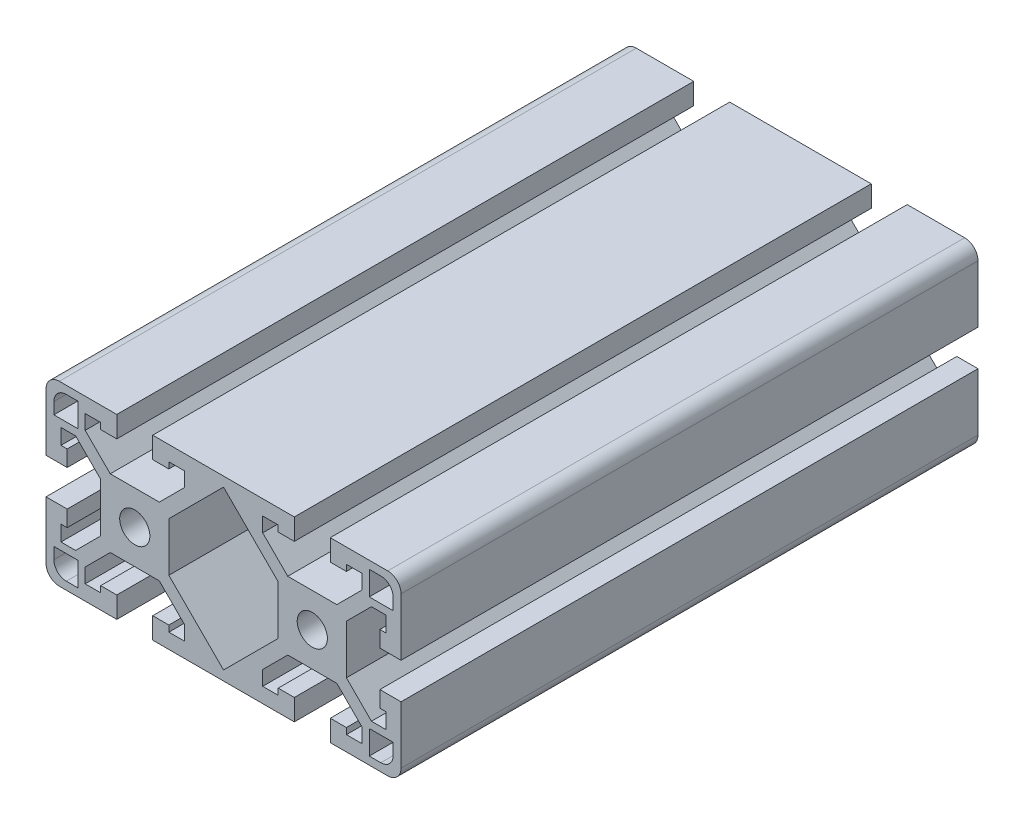
SolidWorks part; units mm, degrees
material "6063-T5"
ref_plane "Front Plane" through (0, 0, 0) normal (0, 0, 1) x (1, 0, 0)
ref_plane "Top Plane" through (0, 0, 0) normal (0, 1, 0) x (1, 0, 0)
ref_plane "Right Plane" through (0, 0, 0) normal (1, 0, 0) x (0, 0, -1)
sketch "Sketch1" plane through (0, 0, 0) normal (0, 1, 0) x (1, 0, 0)
  line L0 (0, 130) -> (0, 0)
  dimension "D1" = 130
other "40 series TS40-80LM-650037(1)"
ref_plane "Plane1" through (0, 0, -130) normal (0, 0, 1) x (0, 1, 0)
sketch "Sketch2" plane through (0, 0, -130) normal (0, 0, 1) x (0, 1, 0)
  line L2 (0, -27.681) -> (-5.5257, -27.681)
  line L3 (-5.5257, -27.681) -> (-11.176, -33.3313)
  line L4 (-7.6835, -36.6218) -> (-11.176, -36.6218)
  line L5 (-20, -37) -> (-20, -24.0488)
  line L6 (-4.0488, -40) -> (-17, -40)
  line L7 (-7.681, -20) -> (-7.681, -25.5257)
  line L8 (-7.681, -25.5257) -> (-13.3313, -31.176)
  line L9 (-16.6218, -31.176) -> (-16.6218, -27.6835)
  line L10 (-7.681, -14.4743) -> (-13.3313, -8.824)
  line L11 (-13.3313, -8.824) -> (-16.6218, -8.824)
  line L12 (-20, -24.0488) -> (-15.2248, -24.0488)
  line L13 (-20, 15.9512) -> (-20, -15.9512)
  line L14 (-5.5257, 12.319) -> (-17.8447, 0)
  line L15 (-5.5257, -12.319) -> (-17.8447, 0)
  line L16 (-7.681, -20) -> (-7.681, -14.4743)
  line L17 (-5.5257, -12.319) -> (0, -12.319)
  line L18 (7.681, -20) -> (7.681, -14.4743)
  line L19 (5.5257, -12.319) -> (17.8447, 0)
  line L20 (20, 15.9512) -> (15.2248, 15.9512)
  line L21 (4.0488, -35.2248) -> (7.6835, -35.2248)
  line L22 (7.681, 14.4743) -> (13.3313, 8.824)
  line L23 (7.6835, -36.6218) -> (7.6835, -35.2248)
  line L24 (4.0488, -35.2248) -> (4.0488, -40)
  line L25 (7.6835, -36.6218) -> (11.176, -36.6218)
  line L26 (11.176, -33.3313) -> (11.176, -36.6218)
  line L27 (7.681, -20) -> (7.681, -25.5257)
  line L28 (4.0488, -40) -> (17, -40)
  line L29 (20, -37) -> (20, -24.0488)
  line L30 (5.5257, -27.681) -> (11.176, -33.3313)
  line L31 (7.681, -25.5257) -> (13.3313, -31.176)
  line L32 (0, -12.319) -> (5.5257, -12.319)
  line L33 (0, -27.681) -> (5.5257, -27.681)
  line L35 (13.3313, 8.824) -> (16.6218, 8.824)
  line L36 (0, 12.319) -> (5.5257, 12.319)
  line L37 (-5.5257, 12.319) -> (0, 12.319)
  line L38 (16.6218, 8.824) -> (16.6218, 12.3165)
  line L39 (15.2248, 15.9512) -> (15.2248, 12.3165)
  line L40 (16.6218, 12.3165) -> (15.2248, 12.3165)
  line L41 (20, 24.0488) -> (15.2248, 24.0488)
  line L42 (0, 27.681) -> (5.5257, 27.681)
  line L43 (-4.0488, 40) -> (-17, 40)
  line L44 (-20, 37) -> (-20, 24.0488)
  line L45 (4.0488, 35.2248) -> (4.0488, 40)
  line L46 (16.6218, 31.176) -> (16.6218, 27.6835)
  line L47 (7.681, 20) -> (7.681, 25.5257)
  line L48 (13.3313, 31.176) -> (16.6218, 31.176)
  line L49 (15.2248, 24.0488) -> (15.2248, 27.6835)
  line L50 (7.681, 20) -> (7.681, 14.4743)
  line L51 (-7.681, 25.5257) -> (-7.681, 14.4743)
  line L52 (16.6218, 27.6835) -> (15.2248, 27.6835)
  line L53 (12.8372, 38.222) -> (12.8372, 32.8372)
  line L54 (20, 37) -> (20, 24.0488)
  line L55 (4.0488, 40) -> (17, 40)
  line L56 (12.8372, 38.222) -> (15.428, 38.222)
  line L57 (18.222, 35.428) -> (18.222, 32.8372)
  line L58 (12.8372, 32.8372) -> (18.222, 32.8372)
  line L59 (0, 27.681) -> (-5.5257, 27.681)
  line L60 (-4.0488, -35.2248) -> (-4.0488, -40)
  line L61 (-16.6218, -8.824) -> (-16.6218, -12.3165)
  line L62 (7.681, -14.4743) -> (13.3313, -8.824)
  line L63 (12.8372, -32.8372) -> (18.222, -32.8372)
  line L64 (20, 15.9512) -> (20, -15.9512)
  line L65 (7.681, 25.5257) -> (13.3313, 31.176)
  line L66 (5.5257, 27.681) -> (11.176, 33.3313)
  line L67 (5.5257, 12.319) -> (17.8447, 0)
  line L68 (-13.3313, -31.176) -> (-16.6218, -31.176)
  line L69 (-11.176, -33.3313) -> (-11.176, -36.6218)
  line L70 (-15.2248, -15.9512) -> (-15.2248, -12.3165)
  line L71 (-12.8372, -38.222) -> (-12.8372, -32.8372)
  line L72 (-12.8372, -38.222) -> (-15.428, -38.222)
  line L73 (-15.2248, -24.0488) -> (-15.2248, -27.6835)
  line L74 (-16.6218, -27.6835) -> (-15.2248, -27.6835)
  line L75 (-18.222, -35.428) -> (-18.222, -32.8372)
  line L76 (-12.8372, -32.8372) -> (-18.222, -32.8372)
  line L77 (-7.6835, -36.6218) -> (-7.6835, -35.2248)
  line L78 (-4.0488, -35.2248) -> (-7.6835, -35.2248)
  line L79 (-20, -15.9512) -> (-15.2248, -15.9512)
  line L80 (-16.6218, -12.3165) -> (-15.2248, -12.3165)
  line L81 (18.222, -35.428) -> (18.222, -32.8372)
  line L82 (12.8372, -38.222) -> (15.428, -38.222)
  line L83 (12.8372, -38.222) -> (12.8372, -32.8372)
  line L84 (16.6218, -12.3165) -> (15.2248, -12.3165)
  line L85 (20, -15.9512) -> (15.2248, -15.9512)
  line L86 (16.6218, -27.6835) -> (15.2248, -27.6835)
  line L87 (15.2248, -24.0488) -> (15.2248, -27.6835)
  line L88 (15.2248, -15.9512) -> (15.2248, -12.3165)
  line L89 (13.3313, -31.176) -> (16.6218, -31.176)
  line L90 (16.6218, -8.824) -> (16.6218, -12.3165)
  line L91 (20, -24.0488) -> (15.2248, -24.0488)
  line L92 (13.3313, -8.824) -> (16.6218, -8.824)
  line L93 (16.6218, -31.176) -> (16.6218, -27.6835)
  line L94 (11.176, 33.3313) -> (11.176, 36.6218)
  line L95 (7.6835, 36.6218) -> (11.176, 36.6218)
  line L96 (7.6835, 36.6218) -> (7.6835, 35.2248)
  line L97 (4.0488, 35.2248) -> (7.6835, 35.2248)
  line L98 (-4.0488, 35.2248) -> (-4.0488, 40)
  line L99 (-4.0488, 35.2248) -> (-7.6835, 35.2248)
  line L100 (-7.6835, 36.6218) -> (-7.6835, 35.2248)
  line L101 (-7.6835, 36.6218) -> (-11.176, 36.6218)
  line L102 (-11.176, 33.3313) -> (-11.176, 36.6218)
  line L103 (-5.5257, 27.681) -> (-11.176, 33.3313)
  line L104 (-18.222, 35.428) -> (-18.222, 32.8372)
  line L105 (-12.8372, 32.8372) -> (-18.222, 32.8372)
  line L106 (-7.681, 25.5257) -> (-13.3313, 31.176)
  line L107 (-13.3313, 31.176) -> (-16.6218, 31.176)
  line L108 (-16.6218, 31.176) -> (-16.6218, 27.6835)
  line L109 (-7.681, 14.4743) -> (-13.3313, 8.824)
  line L110 (-16.6218, 12.3165) -> (-15.2248, 12.3165)
  line L111 (-20, 15.9512) -> (-15.2248, 15.9512)
  line L112 (-15.2248, 15.9512) -> (-15.2248, 12.3165)
  line L113 (-16.6218, 8.824) -> (-16.6218, 12.3165)
  line L114 (-13.3313, 8.824) -> (-16.6218, 8.824)
  line L115 (-16.6218, 27.6835) -> (-15.2248, 27.6835)
  line L116 (-15.2248, 24.0488) -> (-15.2248, 27.6835)
  line L117 (-20, 24.0488) -> (-15.2248, 24.0488)
  line L118 (-12.8372, 38.222) -> (-15.428, 38.222)
  line L119 (-12.8372, 38.222) -> (-12.8372, 32.8372)
  arc A0 (-20, -37) -> (-17, -40) centre (-17, -37) ccw
  arc A1 (-20, 37) -> (-17, 40) centre (-17, 37) cw
  arc A2 (20, 37) -> (17, 40) centre (17, 37) ccw
  arc A3 (-15.428, -38.222) -> (-18.222, -35.428) centre (-15.428, -35.428) cw
  arc A4 (15.428, -38.222) -> (18.222, -35.428) centre (15.428, -35.428) ccw
  arc A5 (15.428, 38.222) -> (18.222, 35.428) centre (15.428, 35.428) cw
  arc A6 (-15.428, 38.222) -> (-18.222, 35.428) centre (-15.428, 35.428) ccw
  arc A7 (20, -37) -> (17, -40) centre (17, -37) cw
  circle A8 centre (0, -20) radius 3.35
  circle A9 centre (0, 20) radius 3.35
  point P1 (-20, 20)
  point P3 (-20, 40)
  point P34 (-20, 0)
  point P51 (20, 0)
  point P76 (0, 40)
  point P77 (20, 40)
  point P143 (20, 20)
  point P144 (20, -20)
  point P145 (-20, -20)
  point P146 (-20, -40)
  point P147 (0, -40)
  point P148 (20, -40)
  point P149 (0, 0)
  dimension "D1" = 6.7
hole_wizard "M8x1.25 Tapped Hole1" positions "Sketch5" profile "Sketch6" tap size "M8x1.25" standard "ANSI Metric"
sketch "Sketch5" plane through (0, 0, 0) normal (0, 0, 1) x (1, 0, 0)
  point P0 (-20, 0)
  point P2 (20, 0)
sketch "Sketch6" plane through (-20, 0, 0) normal (1, 0, 0) x (0, -1, 0)
  line L0 (0, 0) -> (0, 32.0429)
  line L1 (0, 32.0429) -> (3.4, 30)
  line L2 (3.4, 30) -> (3.4, 0)
  line L5 (3.4, 0) -> (0, 0)
  line L10 (0, 32.0429) -> (-3.4, 30) construction
  line L11 (0, -6.35) -> (0, 107.95) construction
  dimension "Tap Drill Dia." = 6.8
  dimension "Tap Drill Depth" = 30
  dimension "Drill Angle" = 118
cosmetic thread "Hole Thread1" parameters "D1"=25, "D2"=8
cosmetic thread "Hole Thread2" parameters "D1"=25, "D2"=8
